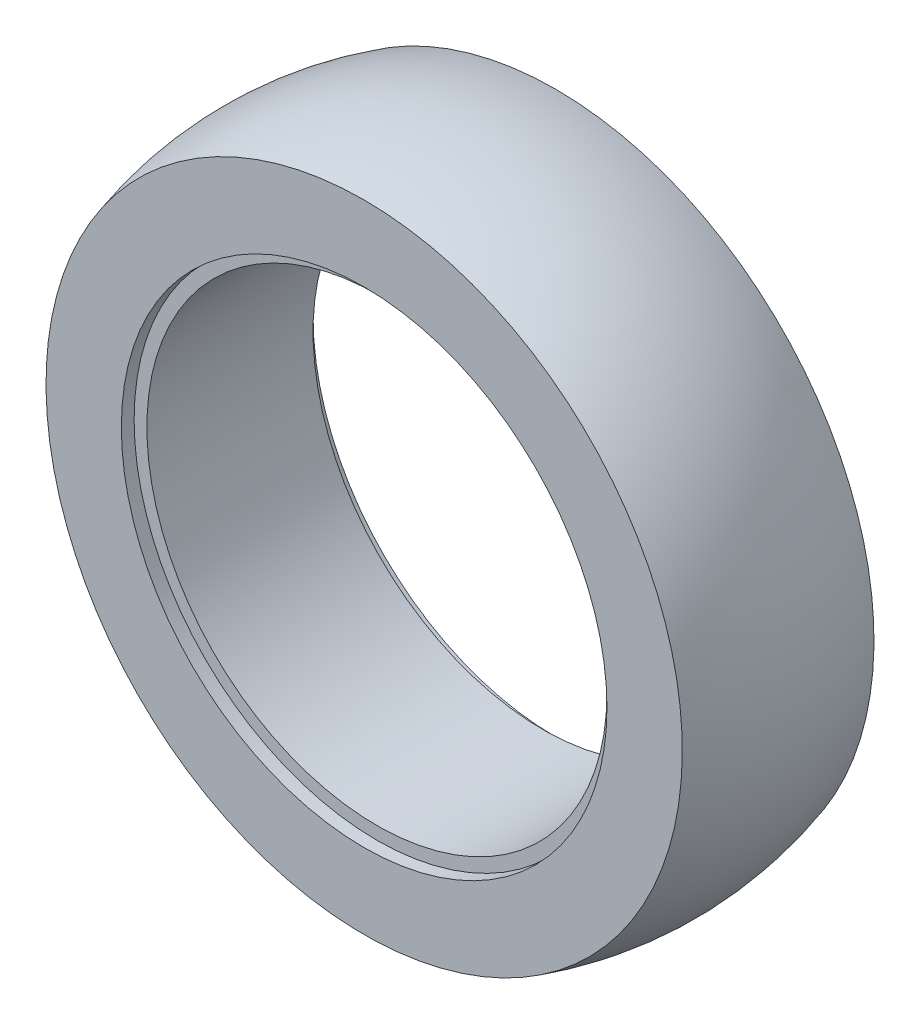
SolidWorks part; units mm, degrees
material "1.2083 (X40Cr14)"
ref_plane "Plan de face" through (0, 0, 0) normal (0, 0, 1) x (1, 0, 0)
ref_plane "Plan de dessus" through (0, 0, 0) normal (0, 1, 0) x (1, 0, 0)
ref_plane "Plan de droite" through (0, 0, 0) normal (1, 0, 0) x (0, 0, -1)
sketch "Esquisse1" plane through (0, 0, 0) normal (1, 0, 0) x (0, 0, -1)
  line L0 (-6.5, 18) -> (6.5, 18)
  line L1 (7.5, 19) -> (7.5, 24.8948)
  line L2 (-7.5, 19) -> (-7.5, 24.8948)
  line L4 (-2.4656, 0) -> (5.0135, 0) construction
  line L5 (-6.5, 18) -> (-6.5, 19)
  line L6 (-6.5, 19) -> (-7.5, 19)
  line L7 (7.5, 19) -> (6.5, 19)
  line L8 (6.5, 19) -> (6.5, 18)
  arc A0 (7.5, 24.8948) -> (-7.5, 24.8948) centre (0, 0) ccw
  dimension "D1" = 52
  dimension "D2" = 1
  dimension "D3" = 7.5
  dimension "D4" = 1
  dimension "D5" = 1
  dimension "D9" = 18
revolve "Révolution1" add sketch "Esquisse1" angle 360 about L4
